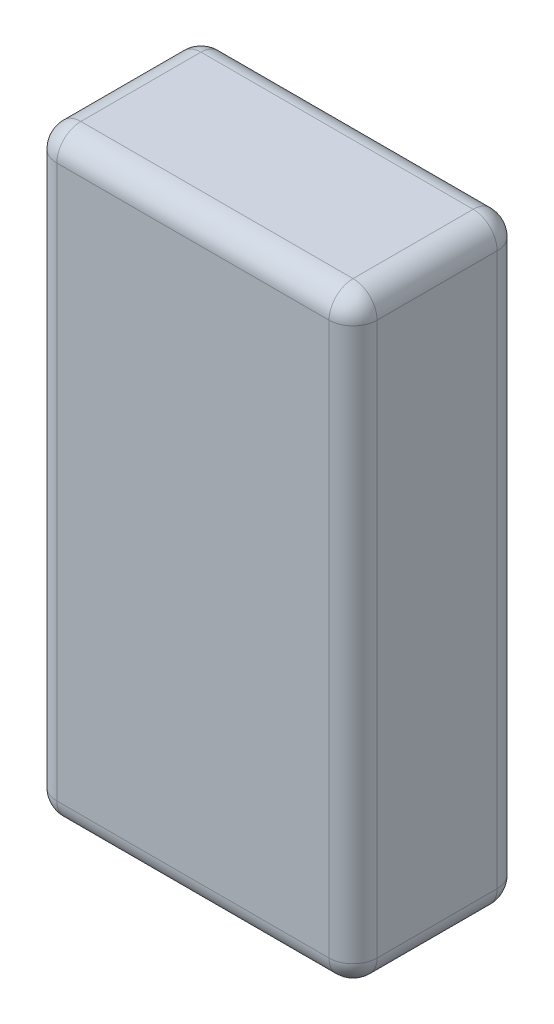
SolidWorks part; units mm, degrees
ref_plane "Front Plane" through (0, 0, 0) normal (0, 0, 1) x (1, 0, 0)
ref_plane "Top Plane" through (0, 0, 0) normal (0, 1, 0) x (1, 0, 0)
ref_plane "Right Plane" through (0, 0, 0) normal (1, 0, 0) x (0, 0, -1)
sketch "Sketch2" plane through (0, 0, 0) normal (0, 0, 1) x (1, 0, 0)
  line L1 (-20, -37.5) -> (20, -37.5)
  line L2 (-20, -37.5) -> (-20, 37.5)
  line L3 (-20, 37.5) -> (20, 37.5)
  line L4 (20, -37.5) -> (20, 37.5)
  line L5 (-20, -37.5) -> (20, 37.5) construction
  line L6 (-20, 37.5) -> (20, -37.5) construction
  point P0 (0, 0)
  dimension "D1" = 40
  dimension "D2" = 75
extrude "Boss-Extrude1" add sketch "Sketch2" along normal blind 21
fillet "Fillet1" radius 3 12 edges at (-20, -37.5, 10.5) (-20, 37.5, 10.5) (20, -37.5, 10.5) (20, 37.5, 10.5) (0, -37.5, 21) (-20, 0, 21) (0, 37.5, 21) (20, 0, 21) (0, 37.5, 0) (-20, 0, 0) (0, -37.5, 0) (20, 0, 0)
